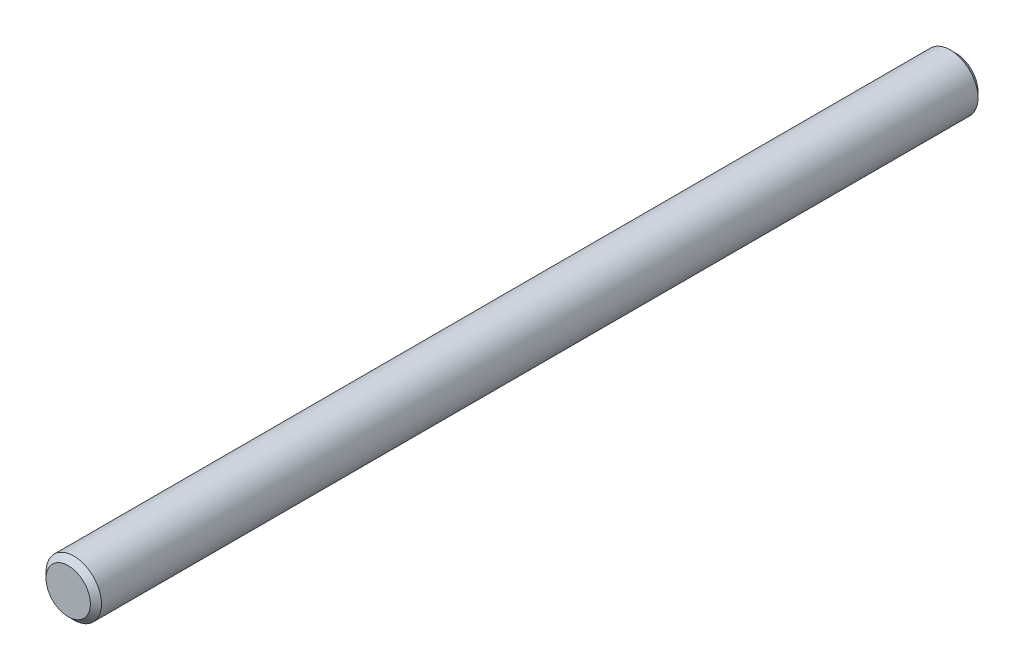
SolidWorks part; units mm, degrees
ref_plane "Front" through (0, 0, 0) normal (0, 0, 1) x (1, 0, 0)
ref_plane "Top" through (0, 0, 0) normal (0, 1, 0) x (1, 0, 0)
ref_plane "Right" through (0, 0, 0) normal (1, 0, 0) x (0, 0, -1)
sketch "Sketch1" plane through (0, 0, 0) normal (0, 0, 1) x (1, 0, 0)
  circle A0 centre (0, 0) radius 3.175
  dimension "dia" = 6.35
sketch "Sketch3" plane through (0, 0, 0) normal (0, 0, 1) x (1, 0, 0)
  circle A0 centre (0, 0) radius 3.175 construction
  circle A1 centre (0, 0) radius 3.175
extrude "Boss-Extrude1" add sketch "Sketch3" along normal mid plane 101.6
sketch "Sketch2" plane through (0, 0, 0) normal (1, 0, 0) x (0, 0, -1)
  line L0 (50.8, 3.175) -> (-50.8, 3.175) construction
  point P0 (-50.8, 3.175)
  point P1 (50.8, 3.175)
  point P2 (-38.1, 3.175)
  point P3 (38.1, 3.175)
  dimension "D1" = 12.7
  dimension "D2" = 12.7
chamfer "Chamfer1" distance 0.635 angle 45 2 edges at (3.175, 0, 50.8) (3.175, 0, -50.8)
equation "\"D1@Chamfer1\" = \"dia@Sketch1\" / 10"
equation "\"D1@Sketch2\"=\"dia@Sketch1\"*2"
equation "\"D2@Sketch2\"=\"D1@Sketch2\""
